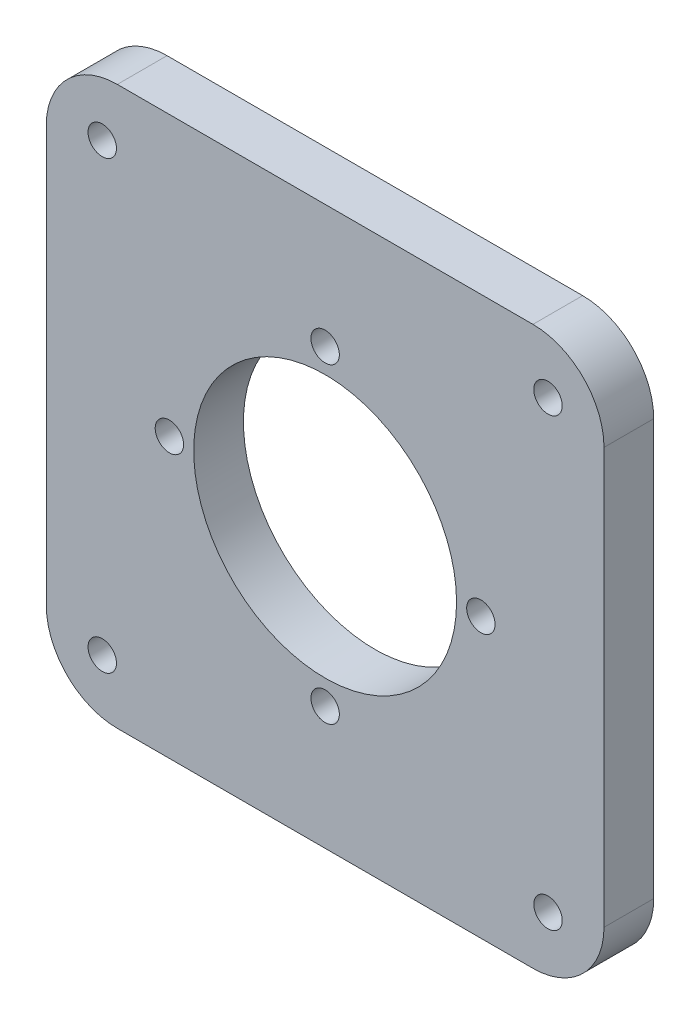
SolidWorks part; units mm, degrees
material "ABS"
ref_plane "Front Plane" through (0, 0, 0) normal (0, 0, 1) x (1, 0, 0)
ref_plane "Top Plane" through (0, 0, 0) normal (0, 1, 0) x (1, 0, 0)
ref_plane "Right Plane" through (0, 0, 0) normal (1, 0, 0) x (0, 0, -1)
sketch "Sketch1" plane through (0, 0, 0) normal (0, 0, 1) x (1, 0, 0)
  line L1 (-39.25, -39.25) -> (39.25, -39.25)
  line L2 (-39.25, -39.25) -> (-39.25, 39.25)
  line L3 (-39.25, 39.25) -> (39.25, 39.25)
  line L4 (39.25, -39.25) -> (39.25, 39.25)
  line L5 (-39.25, -39.25) -> (39.25, 39.25) construction
  line L6 (-39.25, 39.25) -> (39.25, -39.25) construction
  point P0 (0, 0)
  dimension "D1" = 78.5
extrude "Boss-Extrude1" add sketch "Sketch1" along normal mid plane 7
fillet "Fillet1" radius 10 4 edges at (-39.25, -39.25, 0) (39.25, -39.25, 0) (39.25, 39.25, 0) (-39.25, 39.25, 0)
sketch "Sketch2" plane through (0, 0, 3.5) normal (0, 0, 1) x (1, 0, 0)
  line L0 (0, 0) -> (-35355.3391, 35355.3391) construction
  line L1 (0, 0) -> (0, 50000) construction
  line L2 (0, 0) -> (-50000, 0) construction
  circle A0 centre (-31.3713, 31.3713) radius 2
  arc A8 (-29.25, 39.25) -> (-39.25, 29.25) centre (-29.25, 29.25) ccw construction
  circle A9 centre (-31.3713, -31.3713) radius 2
  circle A10 centre (31.3713, 31.3713) radius 2
  circle A11 centre (31.3713, -31.3713) radius 2
  dimension "D2" = 4
  dimension "D3" = 3
  dimension "D1" = 45
extrude "Cut-Extrude1" cut sketch "Sketch2" against normal through all
sketch "Sketch3" plane through (0, 0, 3.5) normal (0, 0, 1) x (1, 0, 0)
  circle A0 centre (0, 0) radius 18.5
  dimension "D1" = 37
extrude "Cut-Extrude2" cut sketch "Sketch3" against normal through all
sketch "Sketch4" plane through (0, 0, 3.5) normal (0, 0, 1) x (1, 0, 0)
  line L1 (0, -21.9203) -> (21.9203, 0) construction
  line L2 (0, -21.9203) -> (-21.9203, 0) construction
  line L3 (-21.9203, 0) -> (0, 21.9203) construction
  line L4 (21.9203, 0) -> (0, 21.9203) construction
  line L5 (0, -21.9203) -> (0, 21.9203) construction
  line L6 (-21.9203, 0) -> (21.9203, 0) construction
  circle A0 centre (0, 21.9203) radius 2
  circle A1 centre (-21.9203, 0) radius 2
  circle A2 centre (0, -21.9203) radius 2
  circle A3 centre (21.9203, 0) radius 2
  point P0 (0, 0)
  dimension "D2" = 4
  dimension "D1" = 31
extrude "Cut-Extrude3" cut sketch "Sketch4" against normal through all
